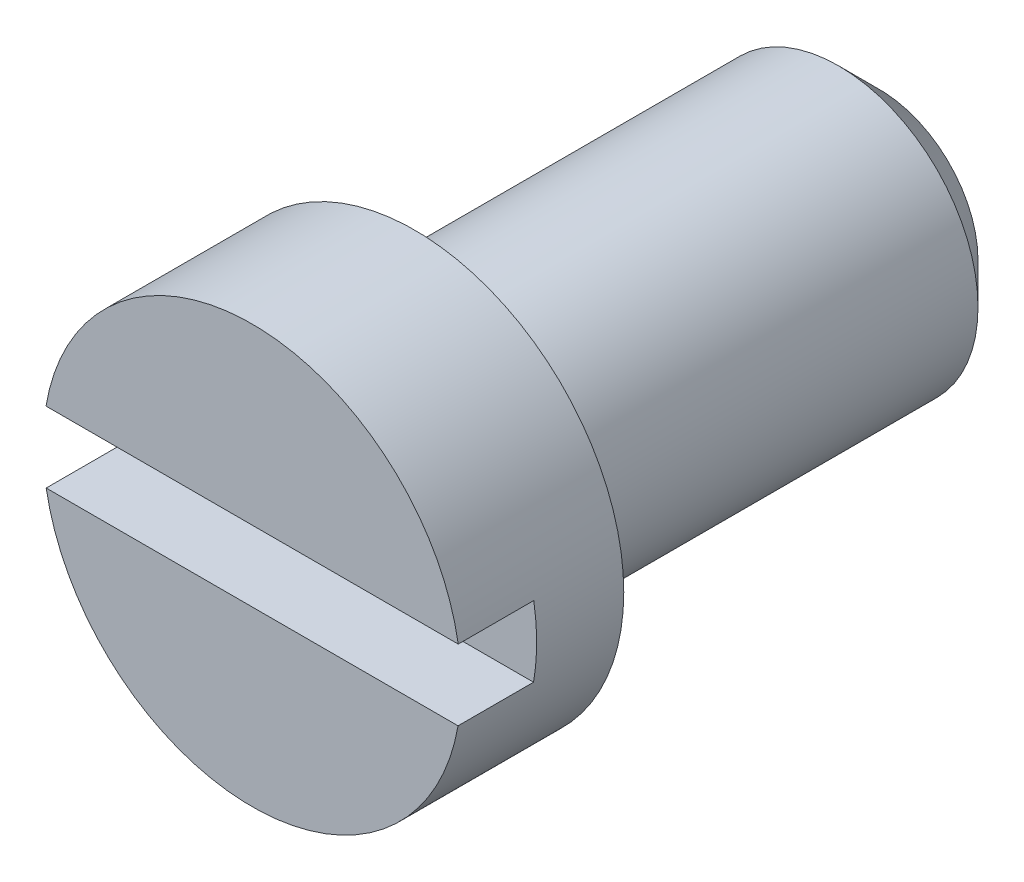
SolidWorks part; units mm, degrees
ref_plane "Спереди" through (0, 0, 0) normal (0, 0, 1) x (1, 0, 0)
ref_plane "Сверху" through (0, 0, 0) normal (0, 1, 0) x (1, 0, 0)
ref_plane "Справа" through (0, 0, 0) normal (1, 0, 0) x (0, 0, -1)
sketch "Эскиз12" plane through (0, 0, 0) normal (0, 0, 1) x (1, 0, 0)
  circle A0 centre (0, 0) radius 9
extrude "Вытянуть3" add sketch "Эскиз12" along normal blind 7
sketch "Эскиз13" plane through (0, 0, 0) normal (0, 0, -1) x (-1, 0, 0)
  circle A0 centre (0, 0) radius 6
extrude "Вытянуть4" add sketch "Эскиз13" along normal blind 20
sketch "Эскиз14" plane through (0, 0, 7) normal (0, 0, 1) x (1, 0, 0)
  line L0 (-9, 0) -> (9, 0) construction
  circle A0 centre (0, 0) radius 9 construction
sketch "Эскиз20" plane through (0, 0, 7) normal (0, 0, 1) x (1, 0, 0)
  line L0 (-9, 0) -> (9, 0) construction
  line L1 (-9.5518, 1.5) -> (9.6443, 1.5)
  line L2 (-9.5518, 1.5) -> (-9.5518, -1.55)
  line L3 (-9.5518, -1.55) -> (9.6443, -1.55)
  line L4 (9.6443, 1.5) -> (9.6443, -1.55)
  dimension "D1" = 1.5
  dimension "D2" = 1.55
extrude "Вырез-Вытянуть8" cut sketch "Эскиз20" against normal blind 3.25
chamfer "Фаска1" distance 1.75 angle 45 1 edges at (-6, 0, -20)
